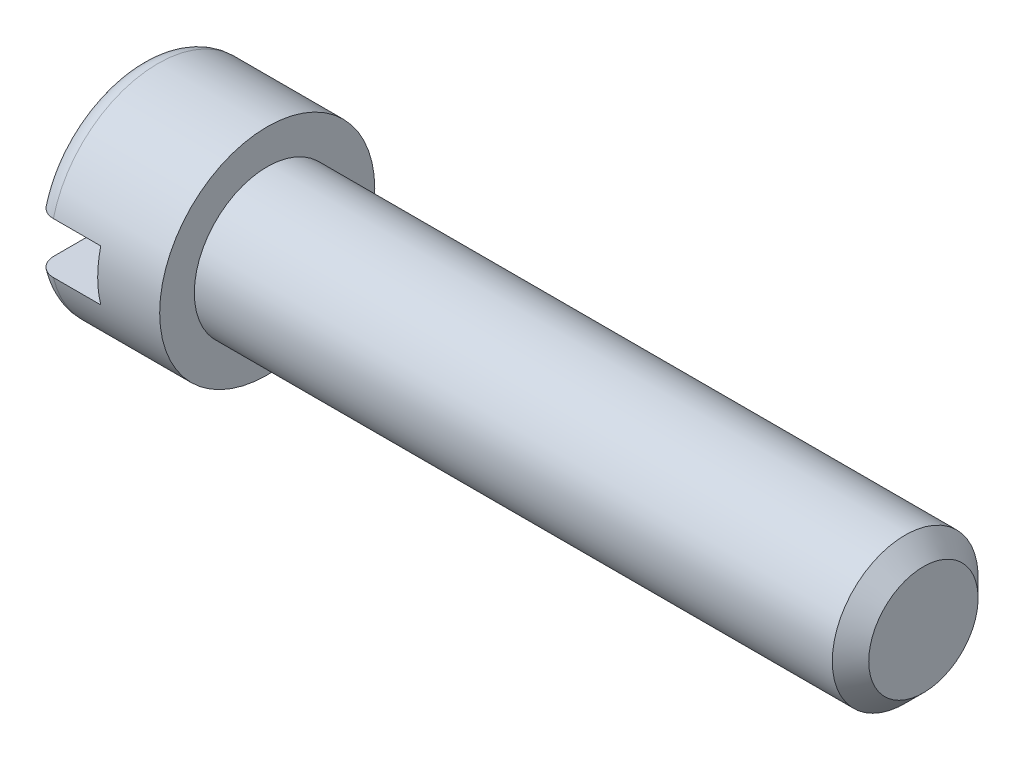
SolidWorks part; units mm, degrees
material "Acier allié"
ref_plane "Plan de face" through (0, 0, 0) normal (0, 0, 1) x (1, 0, 0)
ref_plane "Plan de dessus" through (0, 0, 0) normal (0, 1, 0) x (1, 0, 0)
ref_plane "Plan de droite" through (0, 0, 0) normal (1, 0, 0) x (0, 0, -1)
sketch "Esquisse1" plane through (0, 0, 0) normal (0, 0, 1) x (1, 0, 0)
  line L0 (-6, 0) -> (21.2119, 0) construction
  line L2 (0, 0) -> (0, 2)
  line L3 (0, 2) -> (-18, 2)
  line L4 (-18, 2) -> (-18, 2.95)
  line L5 (-18, 2.95) -> (-21.5, 2.95)
  line L6 (-21.5, 2.95) -> (-21.5, 0)
  line L7 (-21.5, 0) -> (0, 0)
  dimension "D1" = 4
  dimension "D2" = 5.9
  dimension "D3" = 3.5
  dimension "D4" = 18
revolve "Révolution1" add sketch "Esquisse1" angle 360 about L0
cosmetic thread "Représentation de filetage1" parameters "D1"=15, "D2"=3
chamfer "Chanfrein1" distance 0.5 angle 45 1 edges at (0, 0, 2)
fillet "Congé1" radius 0.5 1 edges at (-21.5, 0, 2.95)
sketch "Esquisse2" plane through (0, 0, 0) normal (0, 0, 1) x (1, 0, 0)
  line L0 (-21.5, 2.45) -> (-21.5, -2.45) construction
  line L1 (-21.5, 0.7) -> (-19.7, 0.7)
  line L2 (-21.5, 0.7) -> (-21.5, -0.7)
  line L3 (-21.5, -0.7) -> (-19.7, -0.7)
  line L4 (-19.7, 0.7) -> (-19.7, -0.7)
  line L5 (-19.7, 0) -> (0, 0) construction
  dimension "D1" = 1.4
  dimension "D2" = 1.8
extrude "Enlèv. mat.-Extru.1" cut sketch "Esquisse2" against normal through all and the other way through all
